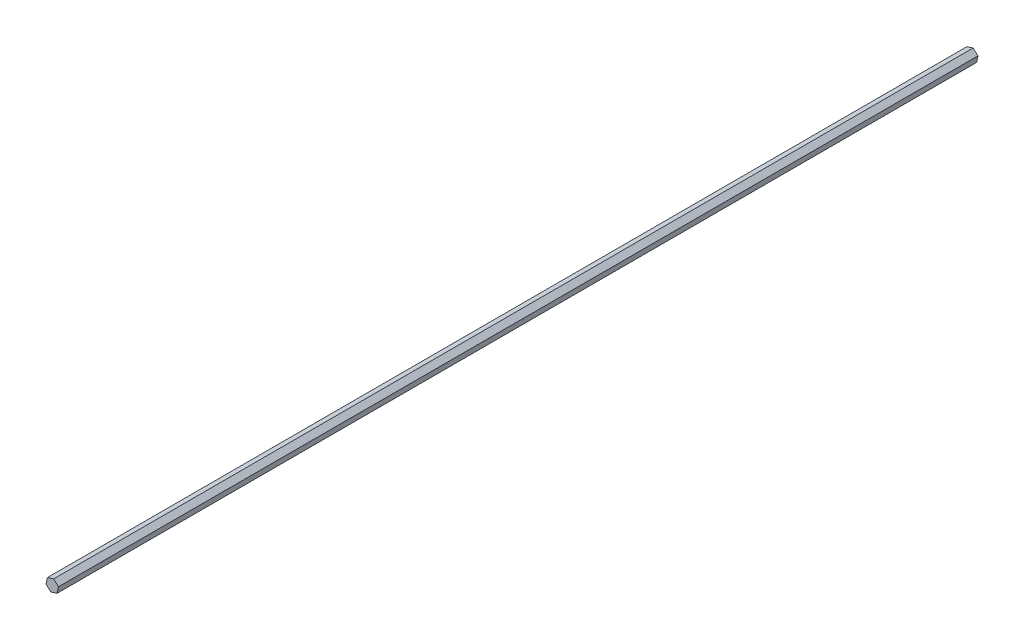
SolidWorks part; units mm, degrees
material "Plain Carbon Steel"
ref_plane "Front Plane" through (0, 0, 0) normal (0, 0, 1) x (1, 0, 0)
ref_plane "Top Plane" through (0, 0, 0) normal (0, 1, 0) x (1, 0, 0)
ref_plane "Right Plane" through (0, 0, 0) normal (1, 0, 0) x (0, 0, -1)
sketch "Sketch1" plane through (0, 0, 0) normal (0, 0, 1) x (1, 0, 0)
  line L1 (2.1373, -1.9404) -> (2.7491, 0.8807)
  line L2 (2.7491, 0.8807) -> (0.6118, 2.8212)
  line L3 (0.6118, 2.8212) -> (-2.1373, 1.9404)
  line L4 (-2.1373, 1.9404) -> (-2.7491, -0.8807)
  line L5 (-2.7491, -0.8807) -> (-0.6118, -2.8212)
  line L6 (-0.6118, -2.8212) -> (2.1373, -1.9404)
  circle A0 centre (0, 0) radius 2.5 construction
extrude "Boss-Extrude1" add sketch "Sketch1" along normal blind 405
